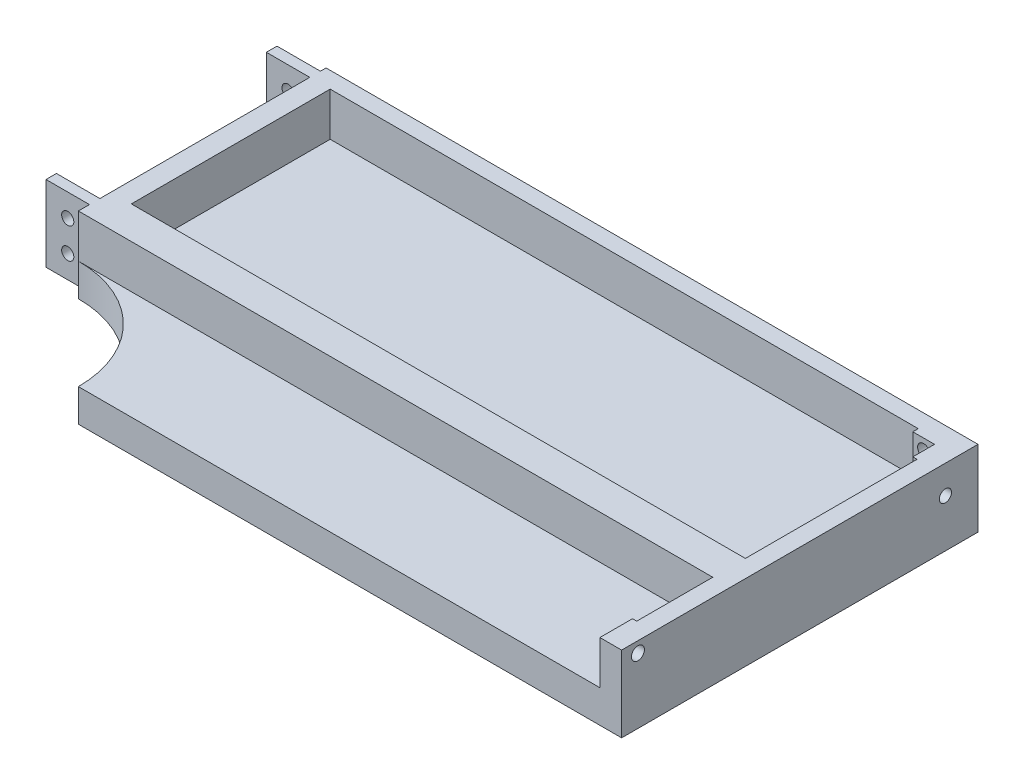
SolidWorks part; units mm, degrees
ref_plane "Front Plane" through (0, 0, 0) normal (0, 0, 1) x (1, 0, 0)
ref_plane "Top Plane" through (0, 0, 0) normal (0, 1, 0) x (1, 0, 0)
ref_plane "Right Plane" through (0, 0, 0) normal (1, 0, 0) x (0, 0, -1)
sketch "Sketch1" plane through (0, 0, 0) normal (0, 1, 0) x (1, 0, 0)
  line L0 (-75, 0) -> (75, 0)
  line L1 (75, 0) -> (75, -82)
  line L2 (-75, 0) -> (-75, -57)
  line L3 (-50, -82) -> (75, -82)
  arc A1 (-75, -57) -> (-50, -82) centre (-75, -82) cw
  point P3 (0, 0)
  dimension "D3" = 25
  dimension "D1" = 150
  dimension "D2" = 57
extrude "Boss-Extrude1" add sketch "Sketch1" along normal blind 2.5 and the other way blind 5
sketch "Sketch2" plane through (0, 2.5, 0) normal (0, 1, 0) x (1, 0, 0)
  line L0 (75, -82) -> (75, 0) construction
  line L1 (-75, 0) -> (75, 0)
  line L2 (-75, 0) -> (-75, -3.75)
  line L3 (-75, -3.75) -> (75, -3.75)
  line L4 (75, 0) -> (75, -3.75)
  line L5 (-75, -57) -> (75, -57)
  line L6 (-75, -57) -> (-75, -49.5)
  line L7 (-75, -49.5) -> (75, -49.5)
  line L8 (75, -57) -> (75, -49.5)
  line L9 (-50, -82) -> (75, -82) construction
  line L10 (-75, -3.75) -> (-70.3131, -3.75)
  line L11 (-75, -3.75) -> (-75, -49.5)
  line L12 (-75, -49.5) -> (-70.3131, -49.5)
  line L13 (-70.3131, -3.75) -> (-70.3131, -49.5)
  line L14 (75, -3.75) -> (70.9743, -3.75)
  line L15 (75, -3.75) -> (75, -49.5)
  line L16 (75, -49.5) -> (70.9743, -49.5)
  line L17 (70.9743, -3.75) -> (70.9743, -49.5)
  line L18 (75, -57) -> (70.9743, -57)
  line L19 (75, -57) -> (75, -82)
  line L20 (75, -82) -> (70.9743, -82)
  line L21 (70.9743, -57) -> (70.9743, -82)
  line M7 (-75, 0) -> (-75, -57)
  line M9 (-50, -82) -> (75, -82)
  line M10 (75, -82) -> (75, 0)
  line M11 (75, 0) -> (-75, 0)
  dimension "D2" = 7.5
  dimension "D3" = 3.75
extrude "Boss-Extrude2" add sketch "Sketch2" along normal blind 10 contours L13 L3 L7 M7 | L7 L5 M7 M10 | L3 M7 M10 M11 | L3 L17 L7 M10 | L5 L21 M9 M10
sketch "Sketch4" plane through (-75, 0, 0) normal (-1, 0, 0) x (0, 0, 1)
  line L0 (0, -5) -> (0, 12.5) construction
  line L1 (54.45, 12.5) -> (52.05, 12.5)
  line L2 (54.45, 12.5) -> (54.45, -5)
  line L3 (54.45, -5) -> (52.05, -5)
  line L4 (52.05, 12.5) -> (52.05, -5)
  line L5 (0, -5) -> (57, -5) construction
  line L6 (57, 12.5) -> (57, 2.5) construction
  line L7 (3.75, 12.5) -> (1.3, 12.5)
  line L8 (3.75, 12.5) -> (3.75, -5)
  line L9 (3.75, -5) -> (1.3, -5)
  line L10 (1.3, 12.5) -> (1.3, -5)
  line L11 (0, 12.5) -> (57, 12.5) construction
  line L13 (57, -5) -> (57, 2.5) construction
  point P15 (0, 0)
  dimension "D1" = 2.55
  dimension "D2" = 4.95
  dimension "D3" = 2.45
  dimension "D4" = 1.3
extrude "Boss-Extrude3" add sketch "Sketch4" along normal blind 10
sketch "Sketch5" plane through (0, 0, 1.3) normal (0, 0, -1) x (-1, 0, 0)
  line L5 (75, 3.75) -> (85, 3.75) construction
  line L6 (75, 12.5) -> (75, -5) construction
  line L7 (85, 12.5) -> (85, -5) construction
  circle A0 centre (80, 7.25) radius 1.4
  circle A2 centre (80, 0.25) radius 1.4
  dimension "D1" = 2.8
  dimension "D2" = 3.5
  dimension "D3" = 5
extrude "Cut-Extrude1" cut sketch "Sketch5" against normal blind 57
sketch "Sketch6" plane through (0, 2.5, 0) normal (0, 1, 0) x (1, 0, 0)
  line L0 (75, 0) -> (65, 0)
  line L5 (75, -82) -> (70, -82)
  line L6 (75, -82) -> (75, -74.5)
  line L7 (75, -74.5) -> (70, -74.5)
  line L8 (70, -82) -> (70, -74.5)
  line L10 (65, 0) -> (65, -5)
  line L11 (65, -5) -> (70, -5)
  line L12 (70, -5) -> (70, -10)
  line L13 (70, -10) -> (75, -10)
  line L14 (75, -82) -> (75, 0) construction
  line L15 (75, -10) -> (75, 0)
  dimension "D1" = 10
  dimension "D2" = 7.5
  dimension "D3" = 5
  dimension "D4" = 5
extrude "Boss-Extrude4" add sketch "Sketch6" along normal blind 10
sketch "Sketch8" plane through (70, 0, 0) normal (-1, 0, 0) x (0, 0, 1)
  line L0 (5, 12.5) -> (10, 12.5) construction
  line L1 (10, 7.5) -> (5, 7.5) construction
  line L2 (10, 12.5) -> (10, 2.5) construction
  line L3 (5, 12.5) -> (5, 2.5) construction
  line L4 (5, 2.5) -> (10, 2.5) construction
  circle A0 centre (7.5, 6) radius 1.4
  point P4 (7.5, 12.5)
  dimension "D1" = 2.8
  dimension "D2" = 3.5
extrude "Cut-Extrude2" cut sketch "Sketch8" against normal blind 5
sketch "Sketch9" plane through (0, 0, 5) normal (0, 0, 1) x (1, 0, 0)
  line L0 (70, 7.5) -> (65, 7.5) construction
  line L1 (70, 12.5) -> (70, 2.5) construction
  line L2 (65, 12.5) -> (65, 2.5) construction
  line L5 (67.5, 7.5) -> (67.5, 12.5) construction
  line L6 (65, 12.5) -> (70, 12.5) construction
  circle A0 centre (67.5, 10) radius 1.4
  point P9 (0, 0)
  point P10 (67.5, 10)
  dimension "D1" = 2.8
extrude "Cut-Extrude3" cut sketch "Sketch9" against normal blind 5
sketch "Sketch10" plane through (70, 0, 0) normal (-1, 0, 0) x (0, 0, 1)
  line L0 (82, 7.5) -> (74.5, 7.5) construction
  line L1 (82, 12.5) -> (82, 2.5) construction
  line L2 (74.5, 12.5) -> (74.5, 2.5) construction
  line L3 (78.25, 12.5) -> (78.25, 7.5) construction
  line L4 (74.5, 12.5) -> (82, 12.5) construction
  circle A0 centre (78.25, 10) radius 1.5
  dimension "D1" = 3
extrude "Cut-Extrude4" cut sketch "Sketch10" against normal blind 5
